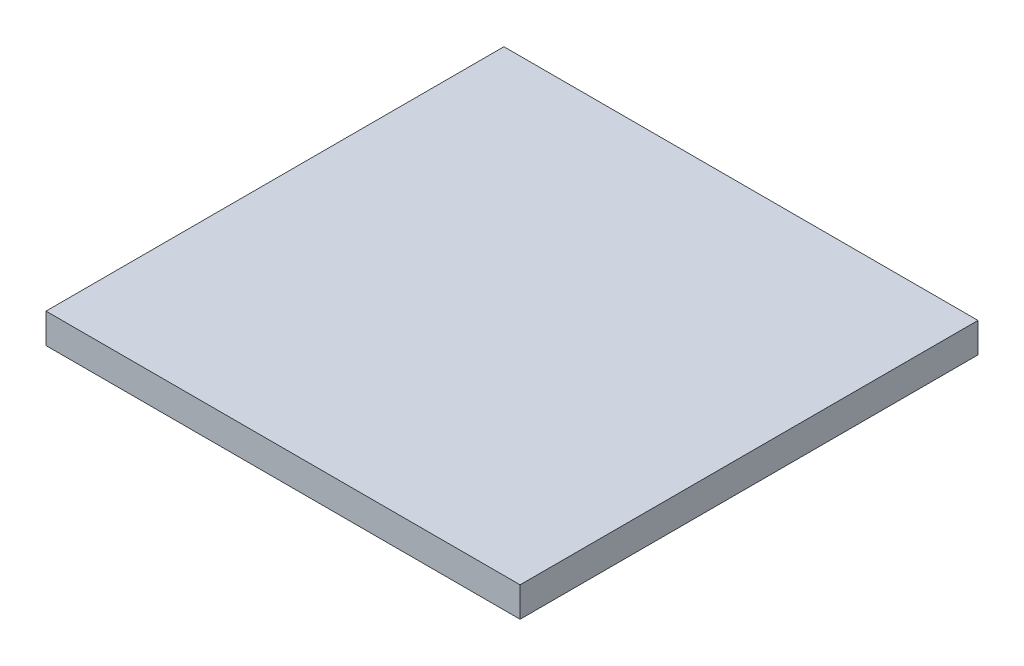
SolidWorks part; units mm, degrees
ref_plane "前视基准面" through (0, 0, 0) normal (0, 0, 1) x (1, 0, 0)
ref_plane "上视基准面" through (0, 0, 0) normal (0, 1, 0) x (1, 0, 0)
ref_plane "右视基准面" through (0, 0, 0) normal (1, 0, 0) x (0, 0, -1)
sketch "草图1" plane through (0, 0, 0) normal (0, 1, 0) x (1, 0, 0)
  line L1 (-119.055, 115) -> (119.055, 115)
  line L2 (-119.055, 115) -> (-119.055, -115)
  line L3 (-119.055, -115) -> (119.055, -115)
  line L4 (119.055, 115) -> (119.055, -115)
  line L5 (-119.055, 115) -> (119.055, -115) construction
  line L6 (-119.055, -115) -> (119.055, 115) construction
  point P0 (0, 0)
  dimension "D1" = 230
  dimension "D2" = 238.11
extrude "凸台-拉伸1" add sketch "草图1" along normal blind 15
